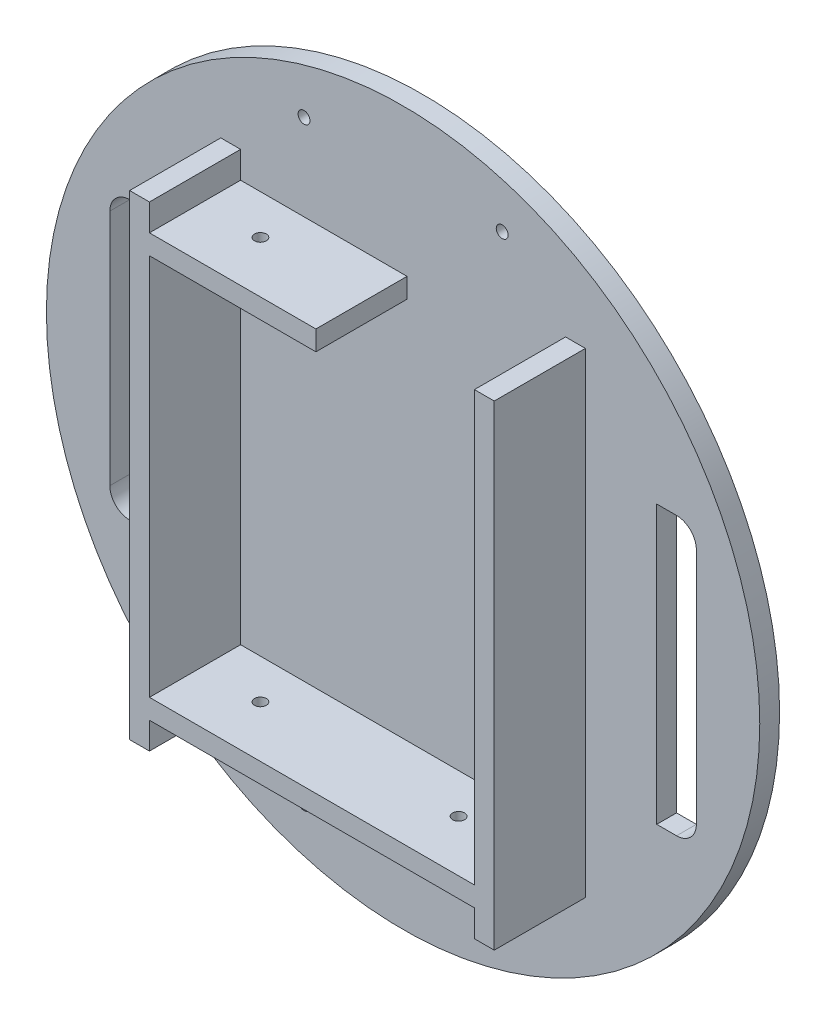
SolidWorks part; units mm, degrees
ref_plane "前基準面" through (0, 0, 0) normal (0, 0, 1) x (1, 0, 0)
ref_plane "上基準面" through (0, 0, 0) normal (0, 1, 0) x (1, 0, 0)
ref_plane "右基準面" through (0, 0, 0) normal (1, 0, 0) x (0, 0, -1)
sketch "草圖1" plane through (0, 0, 0) normal (0, 0, 1) x (1, 0, 0)
  circle A0 centre (0, 0) radius 90
  point P0 (0, 0)
  dimension "D7" = 180
extrude "填料-伸長1" add sketch "草圖1" along normal blind 5
sketch "草圖2" plane through (0, 0, 5) normal (0, 0, 1) x (1, 0, 0)
  line L0 (0, 109.0983) -> (0, -103.3143) construction
  line L1 (-118.0673, 0) -> (130.5826, 0) construction
  circle A0 centre (-25, 75) radius 1.5
  circle A1 centre (-25, -75) radius 1.5
  circle A2 centre (25, 75) radius 1.5
  circle A3 centre (25, -75) radius 1.5
  dimension "D1" = 3
  dimension "D2" = 75
  dimension "D3" = 25
sketch "草圖3" plane through (0, 0, 5) normal (0, 0, 1) x (1, 0, 0)
  line L0 (-64, 35) -> (-64, -35)
  line L1 (-74, 30) -> (-74, -30)
  line L2 (-64, 35) -> (-69, 35)
  line L3 (-64, -35) -> (-69, -35)
  line L4 (0, 127.9588) -> (0, -114.3515) construction
  line L5 (64, -35) -> (69, -35)
  line L6 (64, 35) -> (69, 35)
  line L7 (74, 30) -> (74, -30)
  line L8 (64, 35) -> (64, -35)
  arc A0 (-69, 35) -> (-74, 30) centre (-69, 30) ccw
  arc A1 (-69, -35) -> (-74, -30) centre (-69, -30) cw
  arc A2 (69, -35) -> (74, -30) centre (69, -30) ccw
  arc A3 (69, 35) -> (74, 30) centre (69, 30) cw
  dimension "D1" = 64
  dimension "D2" = 70
  dimension "D3" = 60
  dimension "D4" = 35
  dimension "D5" = 10
  dimension "D6" = 30
  dimension "D7" = 5
  dimension "D8" = 5
extrude "除料-伸長1" cut sketch "草圖3" against normal through all contours A1 L3 L0 L2 A0 L1 | L8 L5 A2 L7 A3 L6
fillet "圓角1" [suppressed] radius 5
extrude "除料-伸長2" cut sketch "草圖2" against normal through all
sketch "草圖4" plane through (0, 0, 5) normal (0, 0, 1) x (1, 0, 0)
  line L0 (0, 97.2889) -> (0, -101.2413) construction
  line L2 (46, 60) -> (46, -60)
  line L3 (-41, 60) -> (-41, -60)
  line L4 (41, -60) -> (46, -60)
  line L5 (41, 60) -> (41, -60)
  line L6 (41, 60) -> (46, 60)
  line L7 (-41, 60) -> (-46, 60)
  line L8 (-41, 60) -> (-41, -60)
  line L9 (-41, -60) -> (-46, -60)
  line L10 (-46, 60) -> (-46, -60)
  line L11 (41, 60) -> (41, -60)
  dimension "D1" = 41
  dimension "D2" = 120
  dimension "D3" = 60
  dimension "D4" = 5
extrude "填料-伸長2" add sketch "草圖4" along normal blind 23 contours L7 L10 L9 L3 | L6 L5 L4 L2
sketch "草圖5" plane through (0, 0, 5) normal (0, 0, 1) x (1, 0, 0)
  line L0 (-41, 60) -> (-41, -60) construction
  line L7 (-41, -48.25) -> (41, -48.25)
  line L8 (-41, -48.25) -> (-41, -53.25)
  line L9 (-41, -53.25) -> (41, -53.25)
  line L10 (41, -48.25) -> (41, -53.25)
  line L11 (41, 60) -> (41, -60) construction
  line L13 (-41, 60) -> (-41, -60) construction
  line L14 (-41, 48.25) -> (1, 48.25)
  line L15 (-41, 48.25) -> (-41, 53.25)
  line L16 (-41, 53.25) -> (1, 53.25)
  line L17 (1, 48.25) -> (1, 53.25)
  line L18 (41, 60) -> (41, -60) construction
  point P0 (0, 0)
  dimension "D3" = 5
  dimension "D5" = 5
  dimension "D6" = 40
extrude "填料-伸長3" add sketch "草圖5" along normal up to surface (23 mm away) up to face at (-43.5, 0, 28)
sketch "草圖6" plane through (0, -53.25, 0) normal (0, -1, 0) x (-1, 0, 0)
  line L0 (41, -28) -> (41, -5) construction
  line L1 (41, -5) -> (-41, -5) construction
  circle A0 centre (26, -15) radius 1.5
  circle A1 centre (-24, -15) radius 1.5
  dimension "D1" = 3
  dimension "D2" = 3
  dimension "D3" = 15
  dimension "D4" = 10
  dimension "D5" = 10
  dimension "D6" = 50
extrude "除料-伸長3" cut sketch "草圖6" against normal through all
